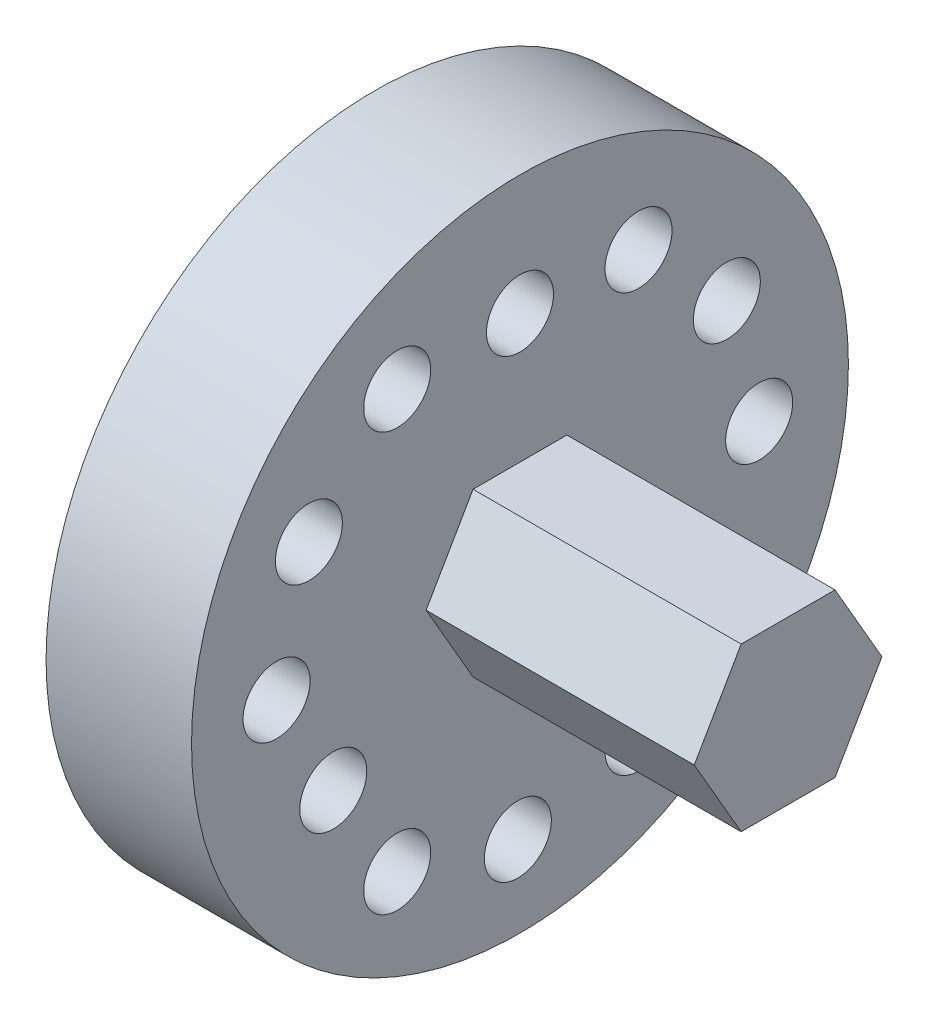
SolidWorks part; units mm, degrees
material "6061 Alloy"
ref_plane "Front Plane" through (0, 0, 0) normal (0, 0, 1) x (1, 0, 0)
ref_plane "Top Plane" through (0, 0, 0) normal (0, 1, 0) x (1, 0, 0)
ref_plane "Right Plane" through (0, 0, 0) normal (1, 0, 0) x (0, 0, -1)
sketch "Sketch1" plane through (0, 0, 0) normal (1, 0, 0) x (0, 0, -1)
  circle A0 centre (0, 0) radius 24.5
  circle A1 centre (0, 0) radius 24.5 construction
  circle A2 centre (0, 0) radius 18 construction
  circle A3 centre (0, 0) radius 15.5452 construction
  circle A4 centre (0, 15.5452) radius 2.5
  circle A5 centre (13.6125, -8.3048) radius 2.5
  circle A6 centre (-13.9272, -8.3048) radius 2.5
  circle A7 centre (8.8426, 15.2337) radius 2.5
  circle A8 centre (15.4311, 8.6452) radius 2.5
  circle A9 centre (17.8426, -0.3548) radius 2.5
  circle A10 centre (8.8426, -15.9432) radius 2.5
  circle A11 centre (-0.1574, -18.3548) radius 2.5
  circle A12 centre (-9.1574, -15.9432) radius 2.5
  circle A13 centre (-18.1574, -0.3548) radius 2.5
  circle A14 centre (-15.7458, 8.6452) radius 2.5
  circle A15 centre (-9.1574, 15.2337) radius 2.5
  point P15 (-0.1574, -0.3548)
  point P20 (-0.1574, -0.3548)
  point P33 (-0.1574, -0.3548)
  dimension "D1" = 49
extrude "Boss-Extrude1" add sketch "Sketch1" along normal blind 10.85
sketch "Sketch3" plane through (10.85, 0, 0) normal (1, 0, 0) x (0, 0, -1)
  circle A0 centre (0, 0) radius 4
  dimension "D1" = 8
sketch "Sketch4" plane through (10.85, 0, 0) normal (1, 0, 0) x (0, 0, -1)
  line L7 (7, -0.1309) -> (3.5, 5.9313)
  line L8 (3.5, 5.9313) -> (-3.5, 5.9313)
  line L9 (-3.5, 5.9313) -> (-7, -0.1309)
  line L10 (-7, -0.1309) -> (-3.5, -6.193)
  line L11 (-3.5, -6.193) -> (3.5, -6.193)
  line L12 (3.5, -6.193) -> (7, -0.1309)
  circle A5 centre (0, -0.1309) radius 6.0622 construction
  dimension "D1" = 7
extrude "Boss-Extrude2" add sketch "Sketch4" along normal blind 20
